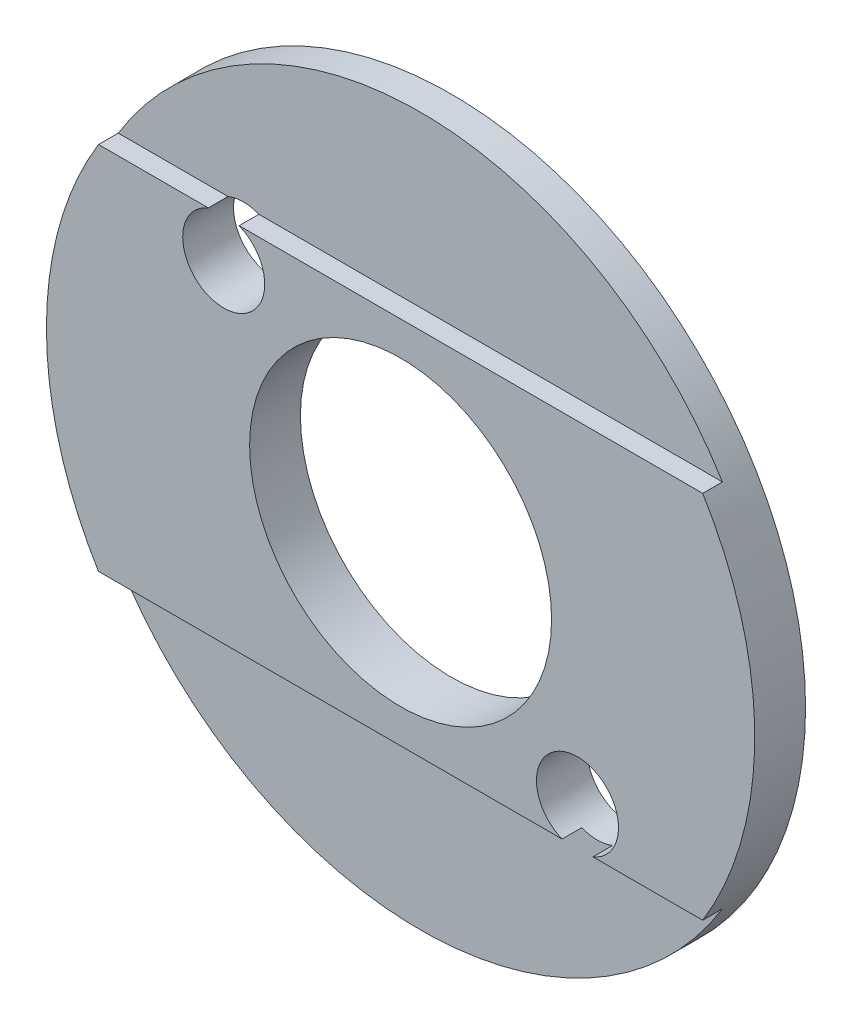
SolidWorks part; units mm, degrees
material "Custom Plastic"
ref_plane "X-Y Datum" through (0, 0, 0) normal (0, 0, 1) x (1, 0, 0)
ref_plane "X-Z Datum" through (0, 0, 0) normal (0, 1, 0) x (1, 0, 0)
ref_plane "Y-Z Datum" through (0, 0, 0) normal (1, 0, 0) x (0, 0, -1)
sketch "Sketch1" plane through (0, 0, 0) normal (0, 0, 1) x (1, 0, 0)
  line L6 (-54.8454, -94.0086) -> (1.429, -94.0086)
  line L7 (-54.8454, -62.2586) -> (1.429, -62.2586)
  line L8 (-54.8454, -63.2586) -> (1.429, -63.2586)
  line L9 (-54.8454, -93.0086) -> (1.429, -93.0086)
  circle A1 centre (-26.7082, -78.1336) radius 28.5
  circle A5 centre (-12.4743, -89.9508) radius 3.3
  circle A6 centre (-40.9421, -66.3164) radius 3.3
  circle A10 centre (-26.7082, -78.1336) radius 12.15
  dimension "D1" = 1
  dimension "D3" = 6.6
  dimension "D4" = 24.3
  dimension "D2" = 1
extrude "Boss-Extrude1" add sketch "Sketch1" along normal blind 1.5875 contours L8 A1 L9 A10 A6 A5
sketch "Sketch2" plane through (0, 0, 0) normal (0, 0, -1) x (-1, 0, 0)
  circle A1 centre (40.9421, -66.3164) radius 3.3
  circle A2 centre (40.9421, -66.3164) radius 3.3
  circle A3 centre (12.4743, -89.9508) radius 3.3
  circle A4 centre (12.4743, -89.9508) radius 3.3
  circle A5 centre (26.7082, -78.1336) radius 28.5
  circle A6 centre (26.7082, -78.1336) radius 28.5
  dimension "D1" = 0
  dimension "D2" = 0
  dimension "D3" = 0
extrude "Boss-Extrude2" add sketch "Sketch2" along normal blind 2.5
